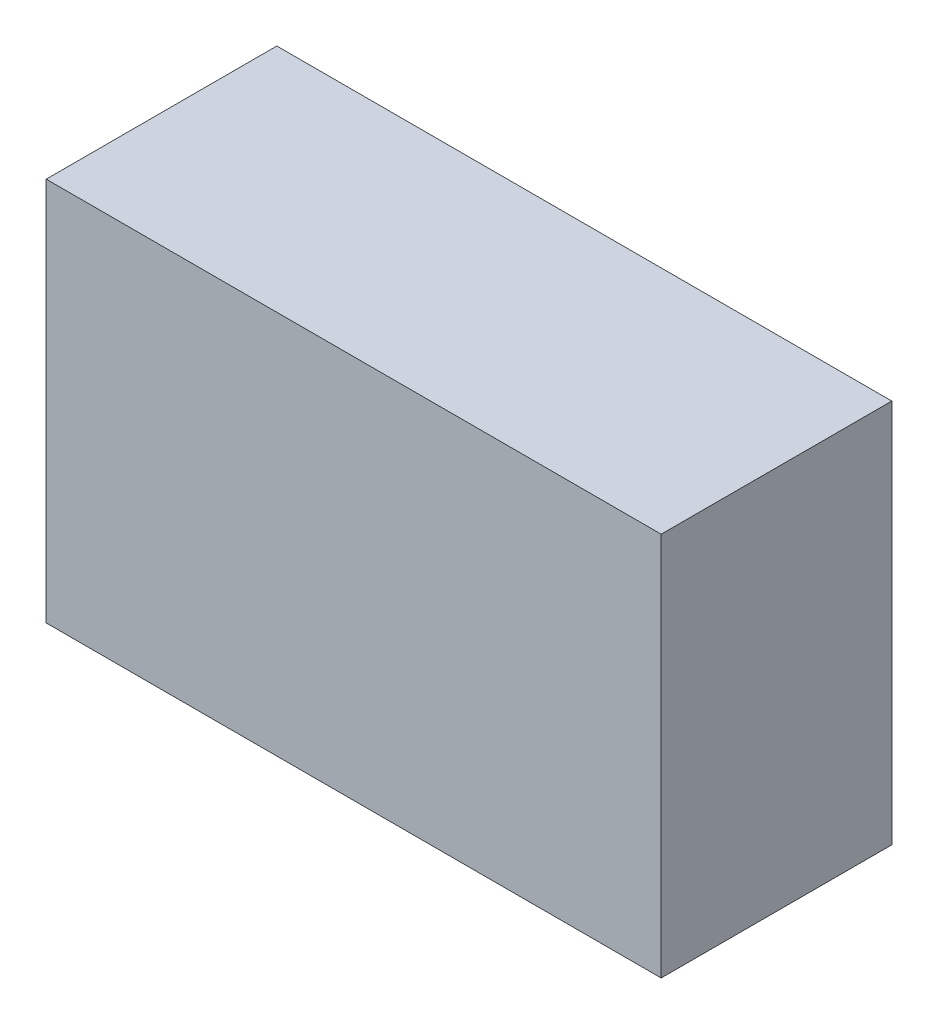
SolidWorks part; units mm, degrees
ref_plane "정면" through (0, 0, 0) normal (0, 0, 1) x (1, 0, 0)
ref_plane "윗면" through (0, 0, 0) normal (0, 1, 0) x (1, 0, 0)
ref_plane "우측면" through (0, 0, 0) normal (1, 0, 0) x (0, 0, -1)
sketch "스케치1" plane through (0, 0, 0) normal (0, 0, 1) x (1, 0, 0)
  line L1 (-8, -5) -> (8, -5)
  line L2 (-8, -5) -> (-8, 5)
  line L4 (8, -5) -> (8, 5)
  line L5 (-8, -5) -> (8, 5) construction
  line L6 (-8, 5) -> (8, -5) construction
  line L11 (-8, 5) -> (8, 5)
  point P0 (0, 0)
  dimension "D1" = 16
  dimension "D2" = 10
extrude "보스-돌출1" add sketch "스케치1" along normal mid plane 6
sketch "스케치2" plane through (0, -5, 0) normal (0, -1, 0) x (1, 0, 0)
  circle A0 centre (0, 0) radius 2
  dimension "D1" = 4
extrude "컷-돌출1" cut sketch "스케치2" against normal offset from surface (5 mm away) 5 up to face at (0, 5, 0)
sketch "스케치3" plane through (0, 0, -3) normal (0, 0, -1) x (-1, 0, 0)
  line L0 (8, 5) -> (8, -5) construction
  line L1 (-8, 5) -> (8, 5)
  line L2 (-8, 5) -> (-8, 0)
  line L3 (-8, 0) -> (8, 0)
  line L4 (8, 5) -> (8, 0)
extrude "보스-돌출2" [suppressed] add sketch "스케치3" along normal blind 5
